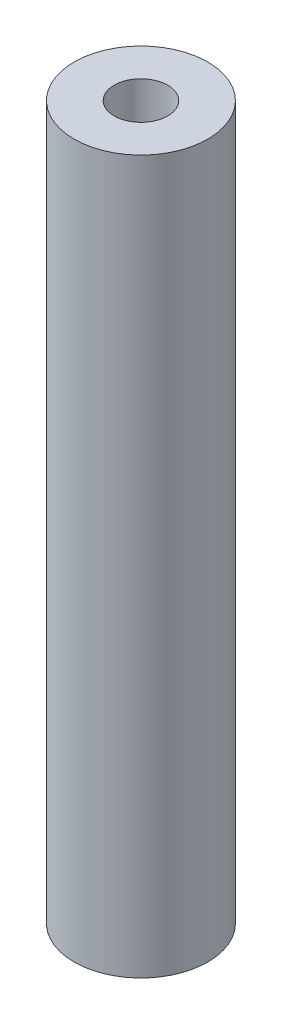
SolidWorks part; units mm, degrees
ref_plane "前视基准面" through (0, 0, 0) normal (0, 0, 1) x (1, 0, 0)
ref_plane "上视基准面" through (0, 0, 0) normal (0, 1, 0) x (1, 0, 0)
ref_plane "右视基准面" through (0, 0, 0) normal (1, 0, 0) x (0, 0, -1)
sketch "草图1" plane through (0, 0, 0) normal (0, 1, 0) x (1, 0, 0)
  circle A0 centre (0, 0) radius 7.5
  dimension "D1" = 15
extrude "凸台-拉伸1" add sketch "草图1" along normal blind 80
sketch "草图2" plane through (0, 80, 0) normal (0, 1, 0) x (1, 0, 0)
  circle A0 centre (0, 0) radius 3
  dimension "D1" = 6
extrude "切除-拉伸1" cut sketch "草图2" against normal blind 20
sketch "草图3" plane through (0, 0, 0) normal (0, -1, 0) x (-1, 0, 0)
  circle A0 centre (0, 0) radius 3
  dimension "D1" = 6
extrude "切除-拉伸2" cut sketch "草图3" against normal blind 20
sketch3d "URDF Reference"
  line L0 (0, 0, 0) -> (10, 0, 0) construction
  line L1 (0, 0, 0) -> (0, 0, -10) construction
  point P0 (0, 0, 0)
